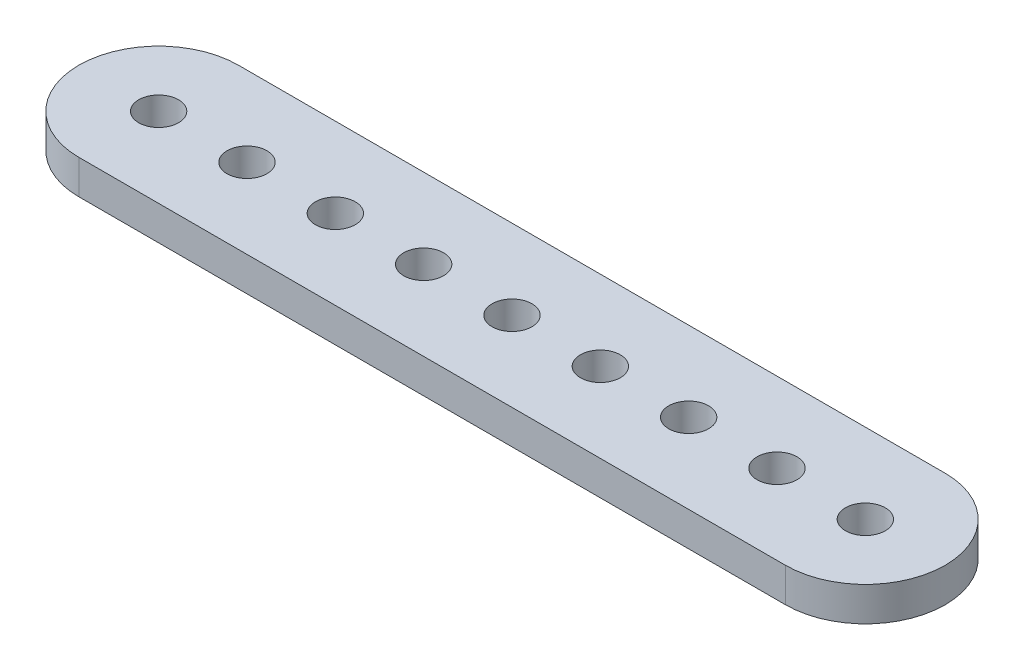
SolidWorks part; units mm, degrees
material "ABS"
ref_plane "Front Plane" through (0, 0, 0) normal (0, 0, 1) x (1, 0, 0)
ref_plane "Top Plane" through (0, 0, 0) normal (0, 1, 0) x (1, 0, 0)
ref_plane "Right Plane" through (0, 0, 0) normal (1, 0, 0) x (0, 0, -1)
other "Center of Mass"
sketch "Sketch1" plane through (0, 0, 0) normal (0, 1, 0) x (1, 0, 0)
  line L0 (-104.8743, 23.4559) -> (19.1257, 23.4559)
  line L1 (-104.8743, -4.5441) -> (19.1257, -4.5441)
  circle A0 centre (-104.8743, 9.4559) radius 3.5
  circle A1 centre (-89.3743, 9.4559) radius 3.5
  circle A2 centre (-73.8743, 9.4559) radius 3.5
  circle A3 centre (-58.3743, 9.4559) radius 3.5
  circle A4 centre (-42.8743, 9.4559) radius 3.5
  circle A5 centre (-27.3743, 9.4559) radius 3.5
  circle A6 centre (-11.8743, 9.4559) radius 3.5
  circle A7 centre (3.6257, 9.4559) radius 3.5
  circle A8 centre (19.1257, 9.4559) radius 3.5
  arc A9 (-104.8743, -4.5441) -> (-104.8743, 23.4559) centre (-104.8743, 9.4559) cw
  arc A10 (19.1257, -4.5441) -> (19.1257, 23.4559) centre (19.1257, 9.4559) ccw
  point P22 (0, 0)
  point P23 (0, 0)
  point P24 (0, 0)
  point P25 (0, 0)
  point P26 (0, 0)
  dimension "D1" = 9
  dimension "D2" = 28
  dimension "D3" = 7
  dimension "D4" = 124
  dimension "D5" = 15.5
extrude "Boss-Extrude1" add sketch "Sketch1" along normal blind 6 contours A2 | A1 | A0 | A6 | A5 | A4 | A3 | A10 L0 A9 L1 | A8 | A7
